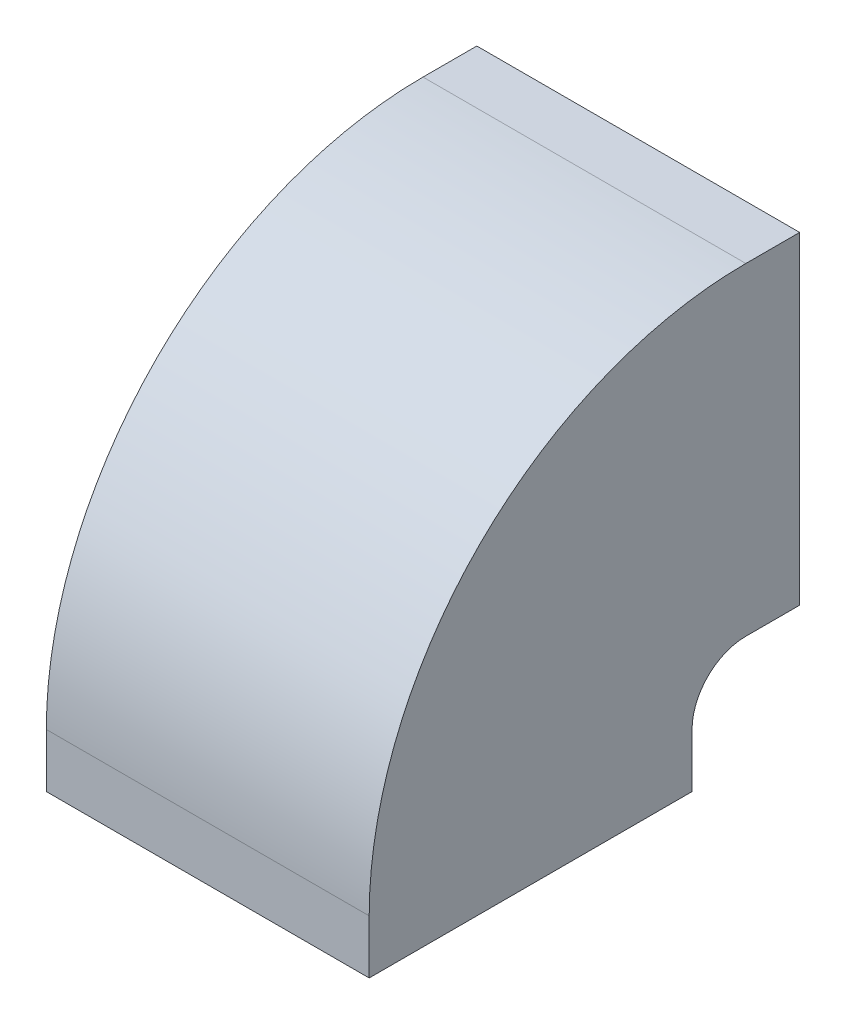
SolidWorks part; units mm, degrees
ref_plane "Front" through (0, 0, 0) normal (0, 0, 1) x (1, 0, 0)
ref_plane "Top" through (0, 0, 0) normal (0, 1, 0) x (1, 0, 0)
ref_plane "Right" through (0, 0, 0) normal (1, 0, 0) x (0, 0, -1)
sketch "Sketch1" plane through (0, 0, 0) normal (1, 0, 0) x (0, 0, -1)
  line L0 (0, 0) -> (152.4, 0)
  line L1 (152.4, 0) -> (152.4, 25.4)
  line L2 (0, 0) -> (0, 25.4)
  line L3 (177.8, 203.2) -> (203.2, 203.2)
  line L4 (203.2, 203.2) -> (203.2, 50.8)
  line L5 (203.2, 50.8) -> (177.8, 50.8)
  arc A0 (0, 25.4) -> (177.8, 203.2) centre (177.8, 25.4) cw
  arc A1 (177.8, 50.8) -> (152.4, 25.4) centre (177.8, 25.4) ccw
  dimension "D1" = 152.4
  dimension "D2" = 25.4
  dimension "D3" = 203.2
extrude "Boss-Extrude1" add sketch "Sketch1" along normal blind 152.4
shell "Shell1" thickness 2.54
sketch "Sketch2" plane through (0, 2.54, 0) normal (0, 1, 0) x (1, 0, 0)
  line L4 (2.54, 149.86) -> (2.54, 2.54)
  line L5 (2.54, 2.54) -> (149.86, 2.54)
  line L6 (149.86, 2.54) -> (149.86, 149.86)
  line L7 (149.86, 149.86) -> (2.54, 149.86)
  line L8 (2.54, 149.86) -> (2.54, 2.54)
  line L9 (2.54, 2.54) -> (149.86, 2.54)
  line L10 (149.86, 2.54) -> (149.86, 149.86)
  line L11 (149.86, 149.86) -> (2.54, 149.86)
  dimension "D1" = 0
extrude "Cut-Extrude2" cut sketch "Sketch2" against normal blind 152.4
